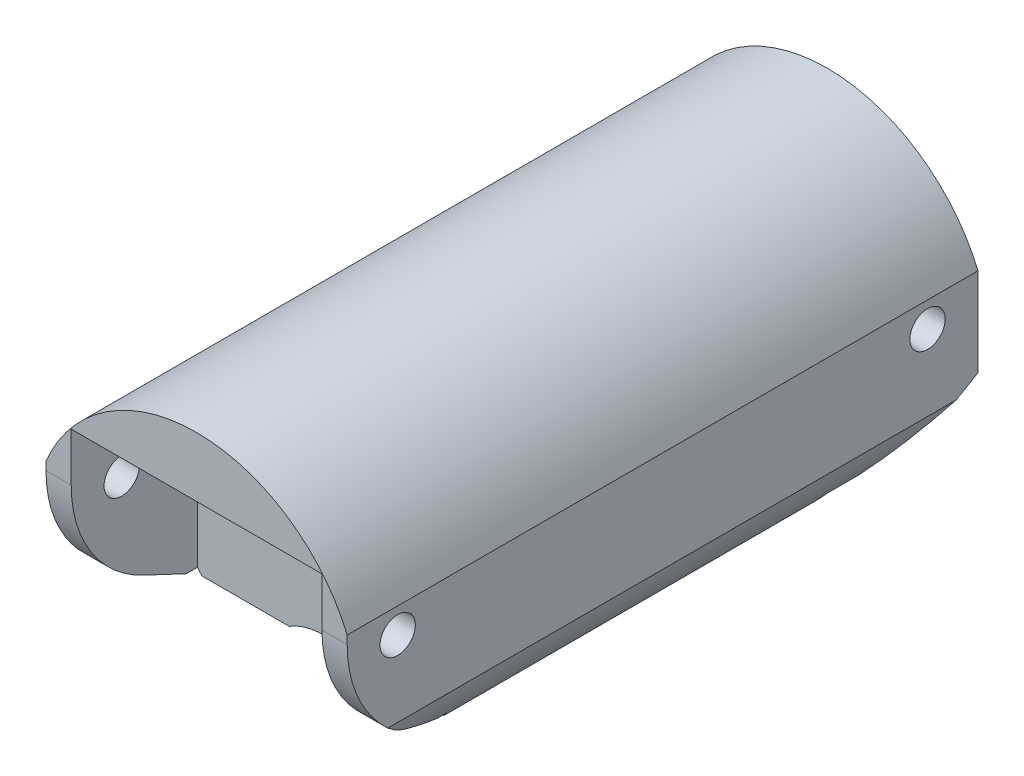
SolidWorks part; units mm, degrees
material "PET"
ref_plane "Front Plane" through (0, 0, 0) normal (0, 0, 1) x (1, 0, 0)
ref_plane "Top Plane" through (0, 0, 0) normal (0, 1, 0) x (1, 0, 0)
ref_plane "Right Plane" through (0, 0, 0) normal (1, 0, 0) x (0, 0, -1)
sketch "Sketch1" plane through (0, 0, 0) normal (0, 0, 1) x (1, 0, 0)
  line L0 (0, 0) -> (0, 5.08)
  line L3 (15.1587, 5.08) -> (15.1587, 0)
  arc A2 (0, 5.08) -> (15.1587, 5.08) centre (7.5794, 1.8999) cw
  arc A3 (0, 0) -> (15.1587, 0) centre (7.5794, 3.1801) ccw
  point P7 (7.5794, -5.0394)
  point P8 (7.5794, 10.1194)
extrude "Boss-Extrude1" add sketch "Sketch1" along normal mid plane 31.75 contours A2 L3 A3 L0
sketch "Sketch2" plane through (0, 0, 0) normal (1, 0, 0) x (0, 0, -1)
  line L4 (15.875, 2.54) -> (-49984.125, 2.54) construction
  line L5 (15.875, 5.08) -> (15.875, 0) construction
  line L6 (-15.875, 5.08) -> (-15.875, 0) construction
  line L7 (-15.875, -5.0394) -> (-15.875, 0.635)
  line L8 (-3.81, -5.0394) -> (-15.875, -5.0394)
  line L9 (-15.875, 0.635) -> (-3.81, -5.0394)
  line L10 (0, -1000) -> (0, 49000) construction
  line L18 (15.875, 0.635) -> (15.875, -5.0394)
  line L19 (-13.335, 1.27) -> (-15.875, 1.27)
  line L21 (-13.335, 3.81) -> (-15.875, 3.81)
  line L22 (-15.875, 1.27) -> (-15.875, 3.81)
  line L23 (-15.0884, 2.54) -> (-15.875, 3.81) construction
  line L24 (-15.0884, 2.54) -> (-15.875, 1.27) construction
  line L27 (13.335, 1.27) -> (15.875, 1.27)
  line L28 (15.875, 1.27) -> (15.875, 3.81)
  line L29 (13.335, 3.81) -> (15.875, 3.81)
  line L30 (15.875, -5.0394) -> (6.0467, -5.0394)
  line L31 (-15.875, -5.0394) -> (15.875, -5.0394) construction
  line L32 (6.0467, -5.0394) -> (15.875, 0.635)
  line L33 (-15.875, 10.1194) -> (-15.875, 5.08) construction
  arc A3 (-13.335, 3.81) -> (-13.335, 1.27) centre (-11.1353, 2.54) cw
  arc A4 (13.335, 3.81) -> (13.335, 1.27) centre (11.1353, 2.54) ccw
  point P0 (-15.0884, 2.54)
  point P11 (15.875, 2.54)
  point P14 (-15.875, 2.54)
  point P26 (-15.875, 2.54)
extrude "Cut-Extrude1" cut sketch "Sketch2" along normal through all
sketch "Sketch3" plane through (0, 0, 15.875) normal (0, 0, 1) x (1, 0, 0)
  line L3 (-12.7761, 2.54) -> (35.5855, 2.54) construction
  line L4 (7.5794, 9.0576) -> (7.5794, -5.0394) construction
  line L5 (16.1544, 2.54) -> (0, 2.54) construction
  line L6 (15.1587, 2.54) -> (0, 2.54) construction
  line L7 (0, 5.08) -> (0, 0) construction
  arc A3 (15.1587, 5.08) -> (0, 5.08) centre (7.5794, 1.8999) ccw construction
  arc A5 (13.918, 4.7488) -> (0.9396, 3.9515) centre (7.5794, 1.8999) ccw
  arc A7 (0, 0) -> (15.1587, 0) centre (7.5794, 3.1801) ccw construction
  arc A9 (13.918, 0.3312) -> (0.9396, 1.1285) centre (7.5794, 3.1801) cw
  arc A11 (15.1587, 5.08) -> (0, 5.08) centre (7.5794, 1.8999) ccw
  arc A12 (4.9537, 8.3343) -> (10.205, 8.3343) centre (7.5794, 10.1194) ccw
  arc A13 (4.9537, -3.2543) -> (10.205, -3.2543) centre (7.5794, -5.0394) cw
  point P14 (7.5794, 6.9444)
  dimension "D1" = 1.27
  dimension "D2" = 3.175
extrude "Cut-Extrude2" cut sketch "Sketch3" against normal through all contours A13 A9
sketch "Sketch4" plane through (0, 0, 0) normal (-1, 0, 0) x (0, 0, 1)
  line L0 (15.875, 1.27) -> (13.335, 1.27) construction
  line L1 (13.335, 3.81) -> (15.875, 3.81) construction
  line L2 (-13.335, 1.27) -> (-15.875, 1.27) construction
  line L3 (-15.875, 3.81) -> (-13.335, 3.81) construction
  line L4 (15.875, 1.27) -> (13.335, 1.27)
  line L5 (13.335, 3.81) -> (15.875, 3.81)
  line L6 (-13.335, 1.27) -> (-15.875, 1.27)
  line L7 (-15.875, 3.81) -> (-13.335, 3.81)
  line L8 (-15.875, 3.81) -> (-15.875, 1.27)
  line L9 (15.875, 3.81) -> (15.875, 1.27)
  arc A0 (11.1353, 0) -> (13.335, 1.27) centre (11.1353, 2.54) ccw construction
  arc A1 (13.335, 3.81) -> (11.1353, 5.08) centre (11.1353, 2.54) ccw construction
  arc A2 (11.1353, 5.08) -> (11.1353, 0) centre (11.1353, 2.54) ccw construction
  arc A3 (-13.335, 1.27) -> (-11.1353, 0) centre (-11.1353, 2.54) ccw construction
  arc A4 (-11.1353, 5.08) -> (-13.335, 3.81) centre (-11.1353, 2.54) ccw construction
  arc A5 (-11.1353, 0) -> (-11.1353, 5.08) centre (-11.1353, 2.54) ccw construction
  arc A6 (11.1353, 0) -> (13.335, 1.27) centre (11.1353, 2.54) ccw
  arc A7 (13.335, 3.81) -> (11.1353, 5.08) centre (11.1353, 2.54) ccw
  arc A8 (11.1353, 5.08) -> (11.1353, 0) centre (11.1353, 2.54) ccw
  arc A9 (-13.335, 1.27) -> (-11.1353, 0) centre (-11.1353, 2.54) ccw
  arc A10 (-11.1353, 5.08) -> (-13.335, 3.81) centre (-11.1353, 2.54) ccw
  arc A11 (-11.1353, 0) -> (-11.1353, 5.08) centre (-11.1353, 2.54) ccw
extrude "Boss-Extrude2" add sketch "Sketch4" against normal up to surface (15.1587 mm away) up to face at (15.1587, 2.54, 0)
ref_plane "Plane1" through (5.08, 0, 0) normal (-1, 0, 0) x (0, 0, 1)
ref_plane "Plane2" through (7.5794, 0, 0) normal (1, 0, 0) x (0, 0, -1)
ref_plane "Plane3" through (0, -5.08, 0) normal (0, 1, 0) x (1, 0, 0)
sketch "Sketch6" plane through (0, -5.08, 0) normal (0, 1, 0) x (1, 0, 0)
  line L0 (15.1587, -15.875) -> (0, -15.875) construction
  line L1 (1.27, -15.875) -> (13.8887, -15.875)
  line L2 (1.27, -15.875) -> (1.27, -9.525)
  line L3 (1.27, -9.525) -> (13.8887, -9.525)
  line L4 (13.8887, -15.875) -> (13.8887, -9.525)
  line L5 (0, -15.875) -> (0, 15.875)
  line L9 (13.8887, -15.875) -> (13.8887, -10.0855)
  line L10 (-14.5241, 0) -> (35.8688, 0) construction
  line L12 (13.8887, 15.875) -> (13.8887, 9.525)
  line L15 (1.27, 9.525) -> (13.8887, 9.525)
  line L17 (1.27, 15.875) -> (13.8887, 15.875)
  line L18 (1.27, 15.875) -> (1.27, 9.525)
  line L20 (15.1587, -14.5248) -> (15.1587, 14.7751) construction
  ellipse E0 centre (7.5794, -21.2865) end of major axis (7.5794, -3.81) minor radius 8.2195 (15.1587, -14.5248) -> (0, -14.5248) ccw construction
  dimension "D1" = 1.27
  dimension "D2" = 1.27
  dimension "D3" = 6.35
extrude "Cut-Extrude3" cut sketch "Sketch6" along normal blind 12.192
sketch "Sketch7" plane through (0, 0, 0) normal (-1, 0, 0) x (0, 0, 1)
  line L0 (14.5248, 0) -> (-14.7751, 0) construction
  line L1 (15.875, 5.08) -> (15.875, 0.635) construction
  line L2 (0, 16.8488) -> (0, -13.3412) construction
  circle A0 centre (13.335, 3.81) radius 0.889
  circle A1 centre (-13.335, 3.81) radius 0.889
  dimension "D1" = 3.81
  dimension "D3" = 1.778
  dimension "D2" = 2.54
extrude "Cut-Extrude4" cut sketch "Sketch7" against normal through all
sketch "Sketch8" plane through (0, 0, -9.525) normal (0, 0, -1) x (-1, 0, 0)
  line L1 (-10.2464, 1.1836) -> (-4.9124, 1.1836) construction
  line L2 (-10.2464, 1.1836) -> (-10.2464, 6.8732) construction
  line L3 (-4.9124, 6.4922) -> (-5.5474, 6.4922) construction
  line L4 (-4.9124, 6.1112) -> (-5.5474, 6.1112)
  line L5 (-4.9124, 6.8732) -> (-5.5474, 6.8732)
  line L6 (-10.2464, 6.8732) -> (-4.9124, 6.8732) construction
  line L7 (-4.9124, 1.1836) -> (-4.9124, 6.8732) construction
  line L8 (-10.2464, 1.1836) -> (-4.9124, 6.8732) construction
  line L9 (-10.2464, 6.8732) -> (-4.9124, 1.1836) construction
  line L10 (-1.27, 7.112) -> (-13.8887, 7.112) construction
  line L11 (-1.27, 7.112) -> (-13.8887, 7.112) construction
  line L12 (-20.0888, -1.8644) -> (7.885, -1.8644) construction
  arc A1 (-4.9124, 6.1112) -> (-4.9124, 6.8732) centre (-4.9124, 6.4922) ccw
  arc A2 (-5.5474, 6.8732) -> (-5.5474, 6.1112) centre (-5.5474, 6.4922) ccw
  arc A3 (-5.1201, -3.0312) -> (-10.0386, -3.0312) centre (-7.5794, -5.0394) ccw construction
  arc A4 (-5.1201, -3.0312) -> (-10.0386, -3.0312) centre (-7.5794, -5.0394) ccw
  point P2 (-5.2299, 6.4922)
  point P7 (-7.5794, 4.0284)
  point P17 (-7.5794, 7.112)
  point P21 (-7.5794, -1.8644)
  dimension "D1" = 0.762
  dimension "D2" = 0.635
  dimension "D3" = 5.334
  dimension "D4" = 5.6896
  dimension "D5" = 3.048
extrude "Cut-Extrude5" cut sketch "Sketch8" against normal blind 15.875 contours L5 A2 L4 A1
fillet "Fillet1" radius 6.35 2 edges at (0.635, 0.635, 15.875) (14.5237, 0.635, 15.875)
sketch "Sketch9" plane through (0, 0, 9.525) normal (0, 0, 1) x (1, 0, 0)
  line L0 (9.2693, -2.3515) -> (13.6589, -2.3515) construction
  line L1 (4.9124, 6.7671) -> (10.2464, 6.7671)
  line L2 (4.9124, 6.7671) -> (4.9124, 1.0775)
  line L3 (4.9124, 1.0775) -> (10.2464, 1.0775)
  line L4 (10.2464, 6.7671) -> (10.2464, 1.0775)
  line L5 (4.9124, 6.7671) -> (10.2464, 1.0775) construction
  line L6 (4.9124, 1.0775) -> (10.2464, 6.7671) construction
  line L7 (9.6114, 6.3861) -> (10.2464, 6.3861) construction
  line L8 (9.6114, 6.7671) -> (10.2464, 6.7671)
  line L9 (9.6114, 6.0051) -> (10.2464, 6.0051)
  line L10 (1.27, 7.112) -> (13.8887, 7.112) construction
  line L11 (1.27, 7.112) -> (13.8887, 7.112)
  arc A0 (9.6114, 6.7671) -> (9.6114, 6.0051) centre (9.6114, 6.3861) ccw
  arc A1 (10.2464, 6.0051) -> (10.2464, 6.7671) centre (10.2464, 6.3861) ccw
  point P0 (7.5794, 3.9223)
  point P9 (9.9289, 6.3861)
  point P19 (7.5794, 7.112)
  dimension "D1" = 5.334
  dimension "D2" = 5.6896
  dimension "D3" = 3.429
  dimension "D4" = 0.635
  dimension "D5" = 0.762
extrude "Cut-Extrude6" cut sketch "Sketch9" against normal blind 17.78 contours L9 A1 L8 A0
sketch "Sketch10" plane through (0, 0, 0) normal (-1, 0, 0) x (0, 0, 1)
  text T0 "Pointer 2\r\n"
extrude "Cut-Extrude7" cut sketch "Sketch10" against normal blind 1
equation "\"D1@Sketch1\"=0.5968"
equation "\"D2@Sketch1\"=0.5968"
equation "\"D1@Boss-Extrude1\"=1.25"
equation "\"D2@Sketch2\"=0.1"
equation "\"D3@Sketch2\"=0.1"
